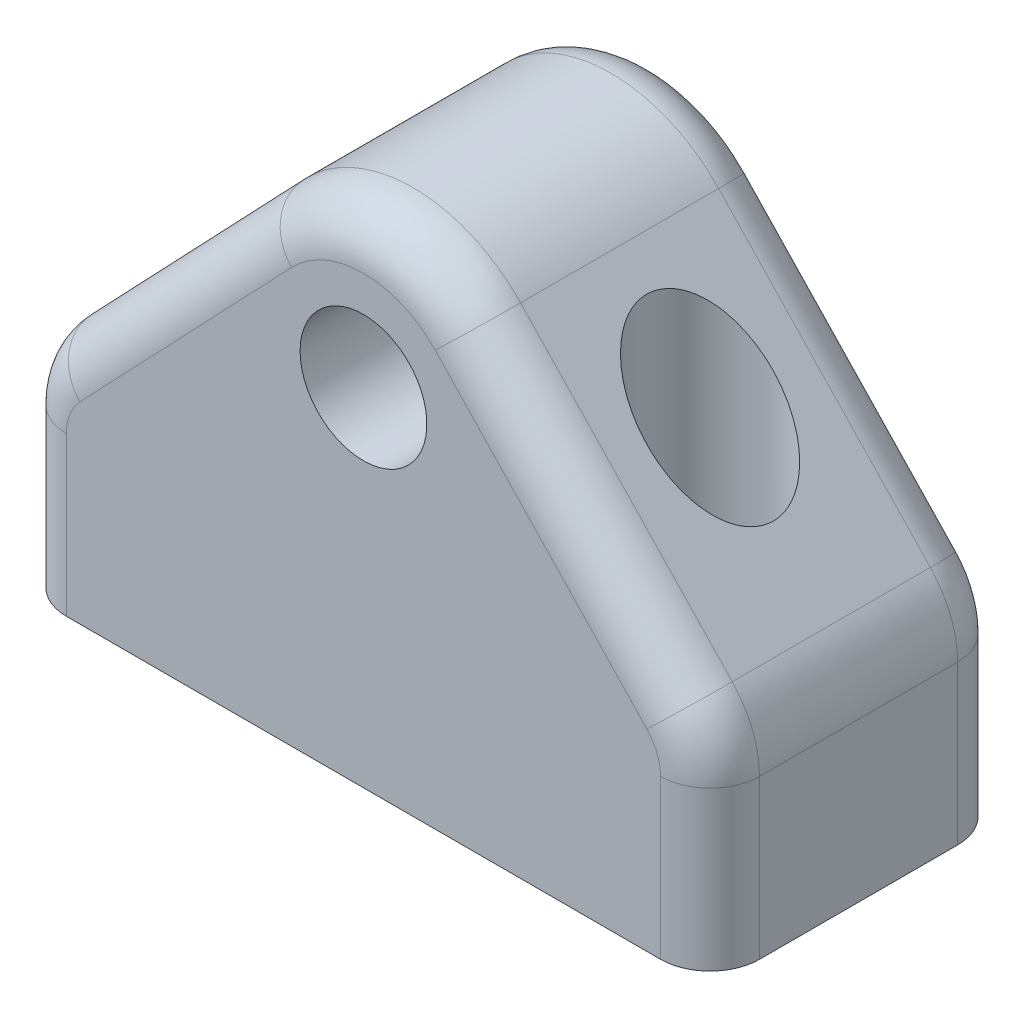
SolidWorks part; units mm, degrees
ref_plane "Front Plane" through (0, 0, 0) normal (0, 0, 1) x (1, 0, 0)
ref_plane "Top Plane" through (0, 0, 0) normal (0, 1, 0) x (1, 0, 0)
ref_plane "Right Plane" through (0, 0, 0) normal (1, 0, 0) x (0, 0, -1)
sketch "Sketch1" plane through (0, 0, 0) normal (0, 0, 1) x (1, 0, 0)
  line L0 (0, 0) -> (0, 5.08)
  line L1 (0.8759, 7.2697) -> (7.6638, 14.397)
  line L2 (14.5612, 14.397) -> (21.3491, 7.2697)
  line L3 (22.225, 5.08) -> (22.225, 0)
  line L4 (22.225, 0) -> (0, 0)
  arc A0 (7.6638, 14.397) -> (14.5612, 14.397) centre (11.1125, 11.1125) cw
  arc A1 (21.3491, 7.2697) -> (22.225, 5.08) centre (19.05, 5.08) cw
  arc A2 (0, 5.08) -> (0.8759, 7.2697) centre (3.175, 5.08) cw
  circle A3 centre (11.1125, 11.1125) radius 2.032
  point P13 (0, 6.35)
  dimension "D1" = 4.7625
  dimension "D5" = 3.175
  dimension "D6" = 4.064
  dimension "D2" = 22.225
  dimension "D3" = 6.35
  dimension "D4" = 11.1125
extrude "Boss-Extrude1" add sketch "Sketch1" along normal blind 9.525
sketch "Sketch2" plane through (0, 0, 0) normal (0, -1, 0) x (1, 0, 0)
  line L0 (0, 9.525) -> (0, 0) construction
  line L1 (0, 4.7625) -> (4.7625, 4.7625) construction
  line L2 (4.7625, 4.7625) -> (17.4625, 4.7625) construction
  line L3 (17.4625, 4.7625) -> (22.225, 4.7625) construction
  line L4 (22.225, 9.525) -> (22.225, 0) construction
  circle A0 centre (4.7625, 4.7625) radius 2.032
  circle A1 centre (17.4625, 4.7625) radius 2.032
  point P7 (0, 4.7625)
  dimension "D1" = 4.064
  dimension "D2" = 12.7
extrude "Cut-Extrude1" cut sketch "Sketch2" against normal through all
fillet "Fillet1" radius 1.5875 14 edges at (22.225, 2.54, 0) (21.9979, 6.2592, 0) (17.9552, 10.8333, 0) (0, 2.54, 0) (0.2271, 6.2592, 0) (4.2698, 10.8333, 0) (22.225, 2.54, 9.525) (21.9979, 6.2592, 9.525) (17.9552, 10.8333, 9.525) (0, 2.54, 9.525) (0.2271, 6.2592, 9.525) (4.2698, 10.8333, 9.525) (11.1125, 15.875, 0) (11.1125, 15.875, 9.525)
